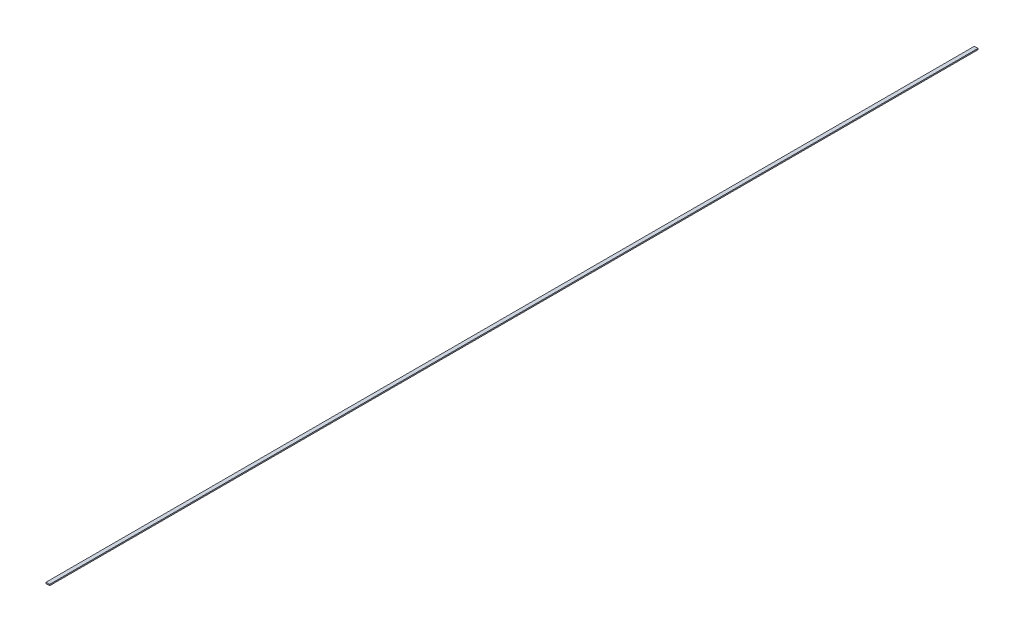
SolidWorks part; units mm, degrees
material "Thornel Mat VMA"
ref_plane "前视基准面" through (0, 0, 0) normal (0, 0, 1) x (1, 0, 0)
ref_plane "上视基准面" through (0, 0, 0) normal (0, 1, 0) x (1, 0, 0)
ref_plane "右视基准面" through (0, 0, 0) normal (1, 0, 0) x (0, 0, -1)
other "Configuration Table"
sketch "草图1" plane through (0, 0, 0) normal (0, 0, 1) x (1, 0, 0)
  line L1 (151.8745, -5.1918) -> (148.8745, -5.1918)
  line L2 (151.8745, -5.1918) -> (151.8745, -6.1918)
  line L3 (151.8745, -6.1918) -> (148.8745, -6.1918)
  line L4 (148.8745, -5.1918) -> (148.8745, -6.1918)
  dimension "D1" = 1
  dimension "D2" = 3
extrude "凸台-拉伸1" add sketch "草图1" along normal blind 759.5
